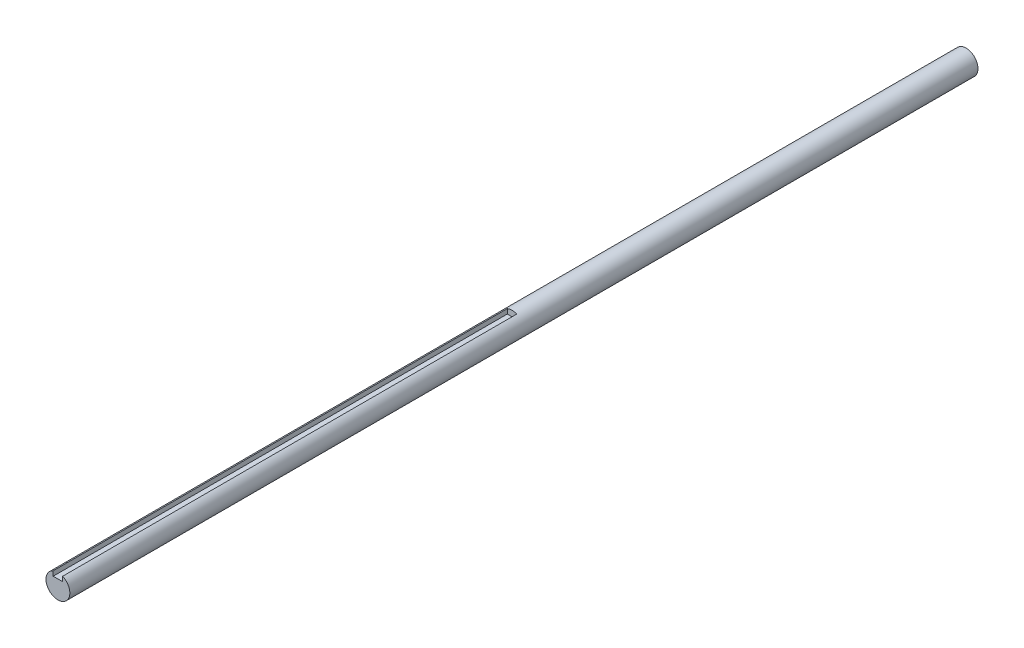
SolidWorks part; units mm, degrees
material "AISI Type 316L stainless steel"
ref_plane "Front Plane" through (0, 0, 0) normal (0, 0, 1) x (1, 0, 0)
ref_plane "Top Plane" through (0, 0, 0) normal (0, 1, 0) x (1, 0, 0)
ref_plane "Right Plane" through (0, 0, 0) normal (1, 0, 0) x (0, 0, -1)
sketch "Sketch1" plane through (0, 0, 0) normal (0, 0, 1) x (1, 0, 0)
  circle A0 centre (0, 0) radius 2
  dimension "D1" = 4
extrude "Boss-Extrude1" add sketch "Sketch1" along normal blind 76.2
sketch "Sketch2" plane through (0, 0, 76.2) normal (0, 0, 1) x (1, 0, 0)
  line L2 (-0.7938, 1.8357) -> (-0.7938, 1.0475)
  line L3 (-0.7938, 1.0475) -> (0.7937, 1.0475)
  line L4 (0.7937, 1.8357) -> (0.7937, 1.0475)
  arc A0 (-0.7938, 1.8357) -> (0.7937, 1.8357) centre (0, 0) ccw
  circle A1 centre (0, 0) radius 2 construction
  point P5 (0, 2)
  dimension "D1" = 1.5875
  dimension "D2" = 0.9525
extrude "Boss-Extrude2" add sketch "Sketch2" along normal blind 76.2 contours A0 L4 L3 L2
